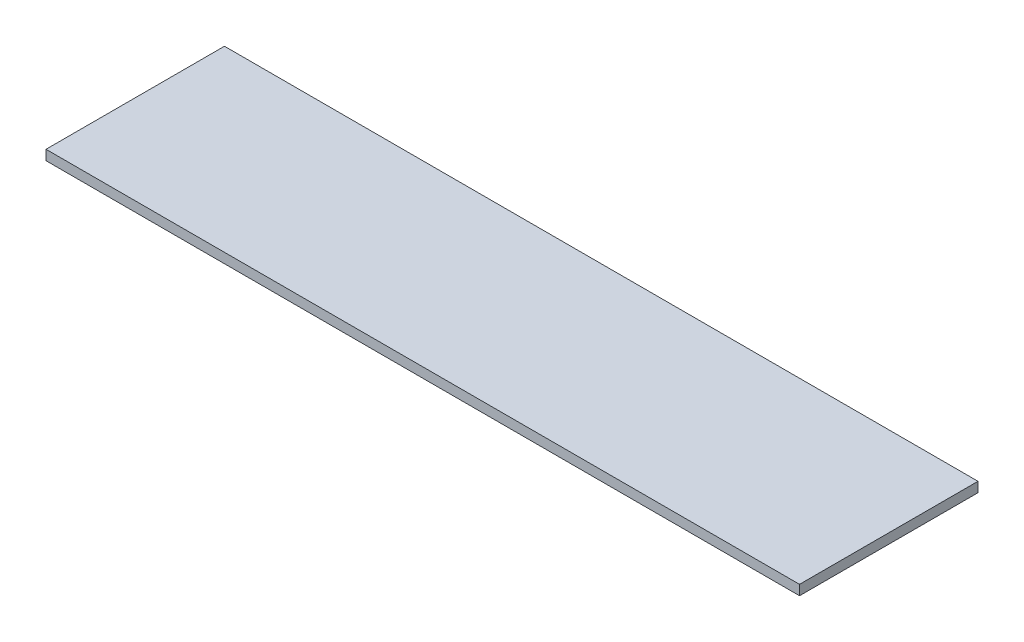
SolidWorks part; units mm, degrees
material "Ti-3Al-8V-6Cr-4Mo-4Zr (SS)"
ref_plane "Front Plane" through (0, 0, 0) normal (0, 0, 1) x (1, 0, 0)
ref_plane "Top Plane" through (0, 0, 0) normal (0, 1, 0) x (1, 0, 0)
ref_plane "Right Plane" through (0, 0, 0) normal (1, 0, 0) x (0, 0, -1)
sketch "Sketch1" plane through (0, 0, 0) normal (0, 1, 0) x (1, 0, 0)
  line L1 (-120.65, 0) -> (120.65, 0)
  line L2 (-120.65, 0) -> (-120.65, 57.15)
  line L3 (-120.65, 57.15) -> (120.65, 57.15)
  line L4 (120.65, 0) -> (120.65, 57.15)
  dimension "D1" = 241.3
  dimension "D2" = 57.15
extrude "Boss-Extrude1" add sketch "Sketch1" along normal blind 3.175
